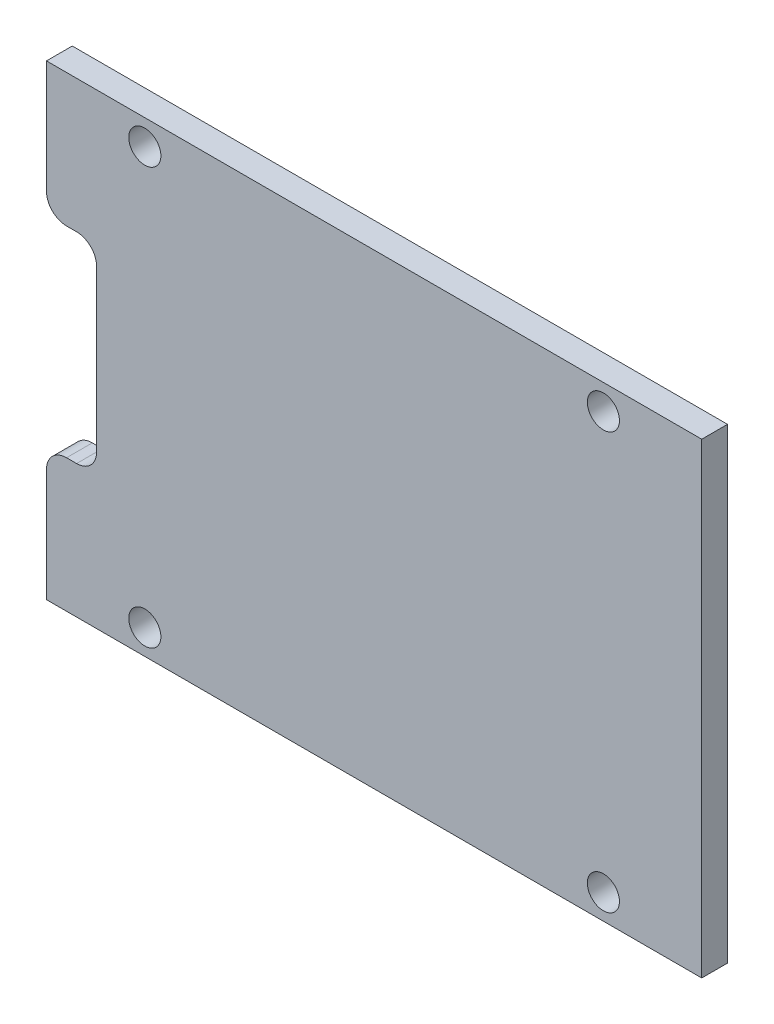
SolidWorks part; units mm, degrees
ref_plane "Front Plane" through (0, 0, 0) normal (0, 0, 1) x (1, 0, 0)
ref_plane "Top Plane" through (0, 0, 0) normal (0, 1, 0) x (1, 0, 0)
ref_plane "Right Plane" through (0, 0, 0) normal (1, 0, 0) x (0, 0, -1)
sketch "Sketch1" plane through (0, 0, 0) normal (0, 0, 1) x (1, 0, 0)
  line L0 (-40, -18.05) -> (25.7, -18.05) construction
  line L2 (-37, 5.4) -> (-40, 5.4) construction
  line L6 (-40, 5.4) -> (25.7, 5.4) construction
  line L7 (-40, 5.4) -> (-40, -41.5) construction
  line L8 (-40, -41.5) -> (25.7, -41.5) construction
  line L9 (25.7, 5.4) -> (25.7, -41.5) construction
  line L18 (-39.8, 5.2) -> (-39.8, -41.3)
  line L19 (-39.8, -41.3) -> (25.5, -41.3) construction
  line L20 (-39.8, -41.3) -> (25.5, -41.3)
  line L21 (25.5, -41.3) -> (25.5, 5.2)
  line L22 (25.5, 5.2) -> (25.5, -41.3) construction
  line L23 (25.5, 5.2) -> (-39.8, 5.2)
  line L24 (-39.8, 5.2) -> (25.5, 5.2) construction
  dimension "D1" = 0.2
extrude "Boss-Extrude1" add sketch "Sketch1" along normal blind 2.57 contours L7 L0 L9 L6 L2 | L0 L7 L8 L9 | L23 L18 L20 L21
sketch "Sketch2" plane through (0, 0, 2.57) normal (0, 0, 1) x (1, 0, 0)
  circle A0 centre (15.7, -38.8) radius 1.6
  circle A1 centre (15.7, 2.7) radius 1.6
  circle A2 centre (-30, 2.7) radius 1.6
  circle A3 centre (-30, -38.8) radius 1.6
extrude "Cut-Extrude2" cut sketch "Sketch2" against normal blind 2.57
sketch "Sketch3" plane through (0, 0, 2.57) normal (0, 0, 1) x (1, 0, 0)
  line L0 (-39.8, 5.2) -> (-39.8, -41.3) construction
  circle A0 centre (-39.8, -18.05) radius 5
extrude "Cut-Extrude3" cut sketch "Sketch3" against normal blind 2.57
sketch "Sketch4" plane through (0, 0, 2.57) normal (0, 0, 1) x (1, 0, 0)
  line L0 (-39.8, -23.05) -> (-39.8, -41.3) construction
  line L1 (-34.8, -8.05) -> (-39.8, -8.05)
  line L2 (-34.8, -8.05) -> (-34.8, -28.05)
  line L3 (-34.8, -28.05) -> (-39.8, -28.05)
  line L4 (-39.8, -8.05) -> (-39.8, -28.05)
  line L5 (-34.8, -8.05) -> (-39.8, -28.05) construction
  line L6 (-34.8, -28.05) -> (-39.8, -8.05) construction
  arc A0 (-39.8, -23.05) -> (-39.8, -13.05) centre (-39.8, -18.05) ccw construction
  point P0 (-34.8, -18.05)
extrude "Cut-Extrude4" cut sketch "Sketch4" against normal blind 10
ref_plane "Plane1" through (-7.15, 0, 0) normal (-1, 0, 0) x (0, 0, 1)
fillet "Fillet1" radius 2 4 edges at (-39.8, -28.05, 1.285) (-39.8, -8.05, 1.285) (-34.8, -28.05, 1.285) (-34.8, -8.05, 1.285)
